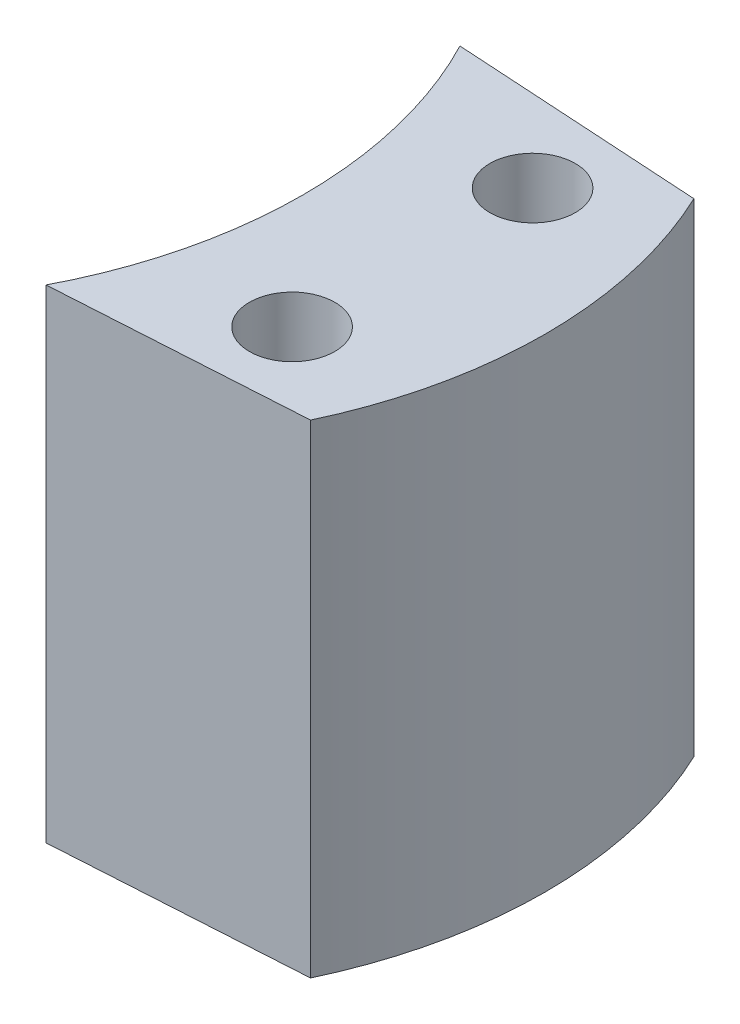
SolidWorks part; units mm, degrees
ref_plane "Front Plane" through (0, 0, 0) normal (0, 0, 1) x (1, 0, 0)
ref_plane "Top Plane" through (0, 0, 0) normal (0, 1, 0) x (1, 0, 0)
ref_plane "Right Plane" through (0, 0, 0) normal (1, 0, 0) x (0, 0, -1)
sketch "Sketch1" plane through (0, 0, 0) normal (0, 1, 0) x (1, 0, 0)
  line L36 (11.0898, 8.53) -> (11.0898, -8.53) construction
  line L38 (7.0898, 5.35) -> (7.0898, -5.35) construction
  line L52 (0, 9.2083) -> (11.0898, 8.53)
  line L53 (0, 0) -> (28.3123, 0) construction
  line L54 (0, -9.2083) -> (11.0898, -8.53)
  line L58 (0, -9.2083) -> (0, 9.2083) construction
  circle A2 centre (7.0898, -5.35) radius 1.9
  circle A6 centre (7.0898, 5.35) radius 1.9
  arc A9 (0, -9.2083) -> (0, 9.2083) centre (-17.7541, 0) ccw
  arc A11 (11.0898, -8.53) -> (11.0898, 8.53) centre (-7, 0) ccw
  point P10 (11.0898, 0)
  point P14 (0, 0)
  point P19 (7.0898, 0)
  point P21 (13, 0)
  dimension "D2" = 13
  dimension "D3" = 3.8
  dimension "D4" = 93.5
  dimension "D6" = 20
  dimension "D5" = 17.06
  dimension "D9" = 10.7
  dimension "D10" = 4
extrude "Boss-Extrude3" add sketch "Sketch1" along normal blind 21.5 contours A9 L52 A11 L54
